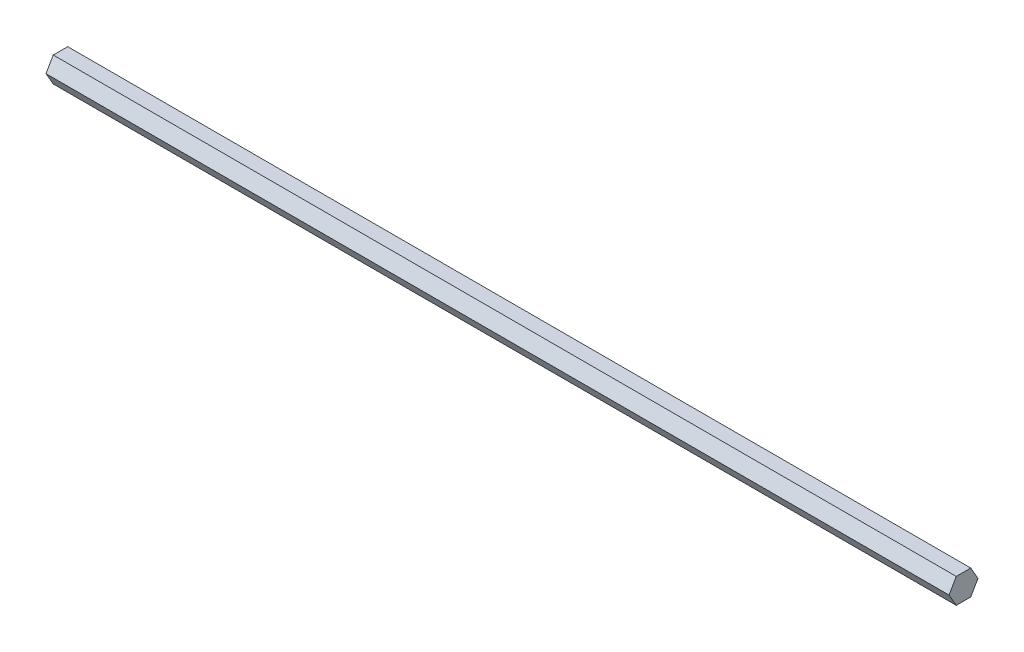
SolidWorks part; units mm, degrees
ref_plane "Front Plane" through (0, 0, 0) normal (0, 0, 1) x (1, 0, 0)
ref_plane "Top Plane" through (0, 0, 0) normal (0, 1, 0) x (1, 0, 0)
ref_plane "Right Plane" through (0, 0, 0) normal (1, 0, 0) x (0, 0, -1)
sketch "Sketch2" plane through (0, 0, 0) normal (1, 0, 0) x (0, 0, -1)
  line L1 (7.3323, 0) -> (3.6662, 6.35)
  line L2 (3.6662, 6.35) -> (-3.6662, 6.35)
  line L3 (-3.6662, 6.35) -> (-7.3323, 0)
  line L4 (-7.3323, 0) -> (-3.6662, -6.35)
  line L5 (-3.6662, -6.35) -> (3.6662, -6.35)
  line L6 (3.6662, -6.35) -> (7.3323, 0)
  circle A0 centre (0, 0) radius 6.35 construction
  dimension "D1" = 12.7
extrude "Boss-Extrude1" add sketch "Sketch2" along normal blind 457.2
sketch "Sketch3" plane through (0, 0, 0) normal (-1, 0, 0) x (0, 0, 1)
  circle A0 centre (0, 0) radius 5.0434
